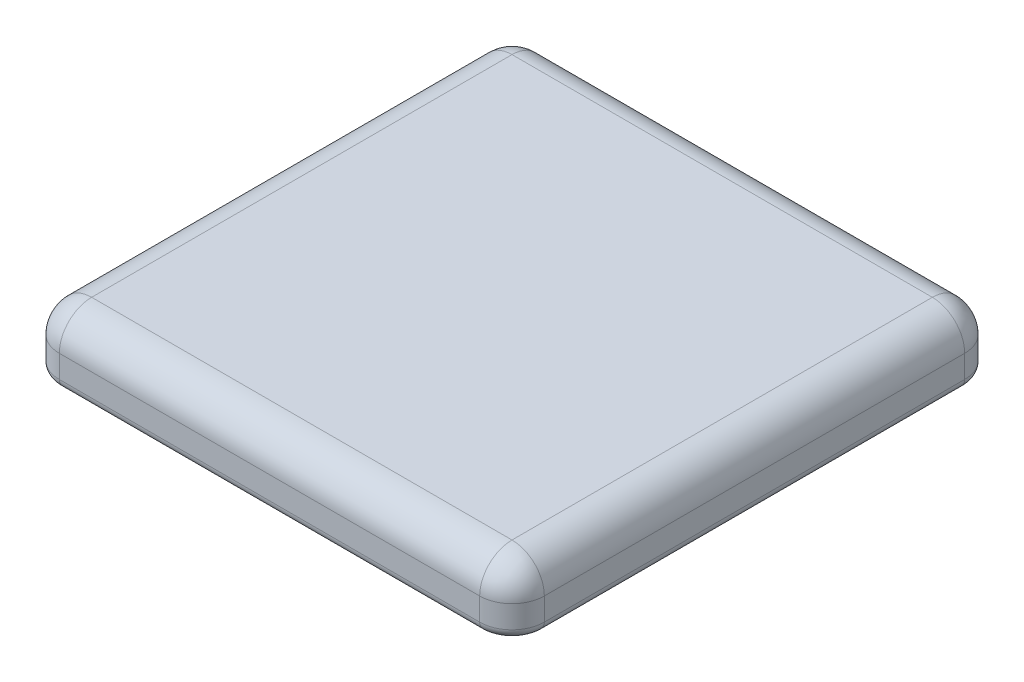
SolidWorks part; units mm, degrees
ref_plane "前视基准面" through (0, 0, 0) normal (0, 0, 1) x (1, 0, 0)
ref_plane "上视基准面" through (0, 0, 0) normal (0, 1, 0) x (1, 0, 0)
ref_plane "右视基准面" through (0, 0, 0) normal (1, 0, 0) x (0, 0, -1)
other "Configuration Table"
sketch "草图1" plane through (0, 0, 0) normal (0, 1, 0) x (1, 0, 0)
  line L0 (23.0286, 0) -> (38.0286, 0)
  line L1 (38.0286, 0) -> (38.0286, 15)
  line L2 (38.0286, 15) -> (23.0286, 15)
  line L3 (23.0286, 15) -> (23.0286, 0)
extrude "凸台-拉伸1" add sketch "草图1" along normal blind 2
fillet "圆角1" radius 1 8 edges at (30.5286, 2, 0) (38.0286, 2, -7.5) (23.0286, 2, -7.5) (30.5286, 2, -15) (38.0286, 1, -15) (23.0286, 1, -15) (38.0286, 1, 0) (23.0286, 1, 0)
sketch "草图2" plane through (0, 0, 0) normal (0, -1, 0) x (1, 0, 0)
  line L0 (28.2786, -9) -> (27.0786, -6) construction
  line L2 (32.7786, -6) -> (33.9786, -6)
  line L3 (32.7786, -6) -> (32.7786, -9)
  line L4 (32.7786, -9) -> (33.9786, -9)
  line L5 (33.9786, -6) -> (33.9786, -9)
  line L6 (32.7786, -6) -> (33.9786, -9) construction
  line L7 (32.7786, -9) -> (33.9786, -6) construction
  line L8 (28.2786, -6) -> (27.0786, -9) construction
  line L9 (27.0786, -6) -> (27.0786, -9)
  line L10 (28.2786, -9) -> (27.0786, -9)
  line L11 (28.2786, -6) -> (28.2786, -9)
  line L12 (28.2786, -6) -> (27.0786, -6)
extrude "凸台-拉伸2" add sketch "草图2" along normal blind 4
fillet "圆角2" radius 0.3 24 edges at (27.6786, 0, -6) (27.0786, 0, -7.5) (27.6786, 0, -9) (28.2786, 0, -7.5) (33.3786, 0, -6) (32.7786, 0, -7.5) (33.3786, 0, -9) (33.9786, 0, -7.5) (33.3786, -4, -9) (32.7786, -4, -7.5) (33.3786, -4, -6) (33.9786, -4, -7.5) (27.6786, -4, -9) (27.0786, -4, -7.5) (27.6786, -4, -6) (28.2786, -4, -7.5) (23.3215, 0, -14.7071) (23.0286, 0, -7.5) (23.3215, 0, -0.2929) (30.5286, 0, 0) (37.7357, 0, -0.2929) (38.0286, 0, -7.5) (37.7357, 0, -14.7071) (30.5286, 0, -15)
